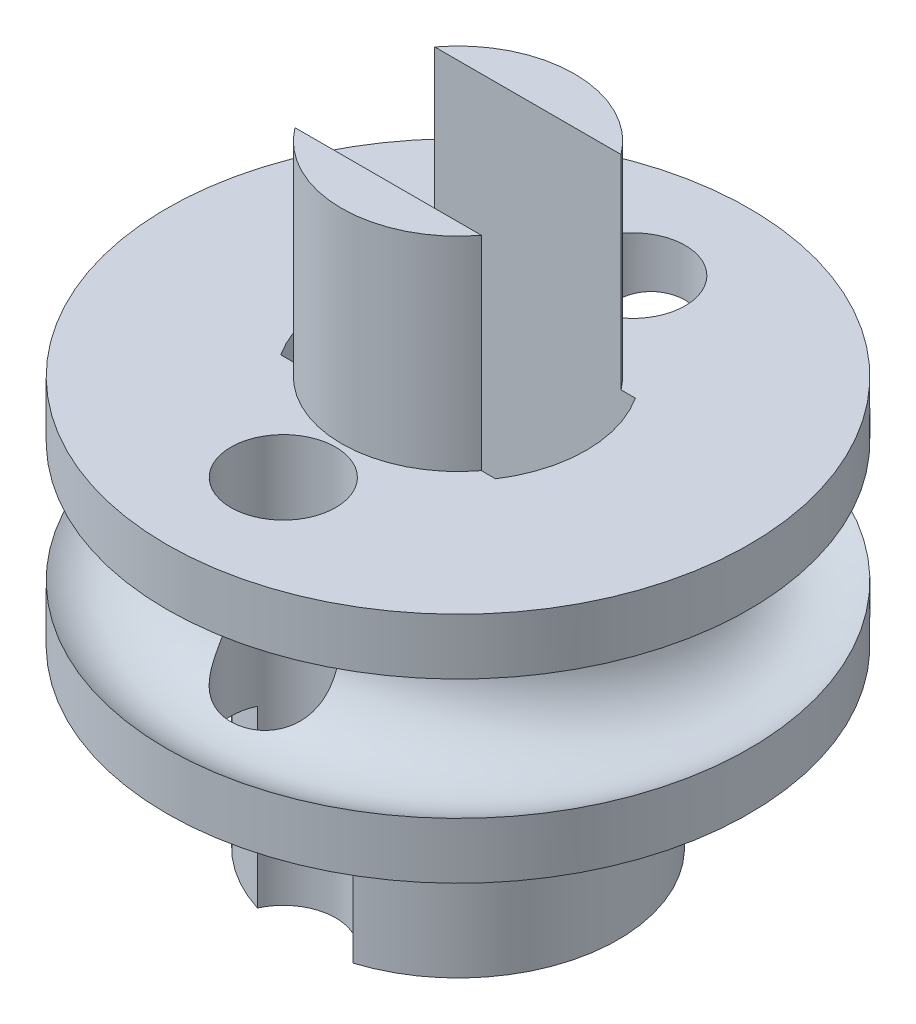
SolidWorks part; units mm, degrees
ref_plane "前视基准面" through (0, 0, 0) normal (0, 0, 1) x (1, 0, 0)
ref_plane "上视基准面" through (0, 0, 0) normal (0, 1, 0) x (1, 0, 0)
ref_plane "右视基准面" through (0, 0, 0) normal (1, 0, 0) x (0, 0, -1)
other "Configuration Table"
sketch "草图1" plane through (0, 0, 0) normal (0, 1, 0) x (1, 0, 0)
  circle A0 centre (0, 0) radius 2.75
  dimension "D1" = 5.5
extrude "凸台-拉伸1" add sketch "草图1" along normal blind 7
sketch "草图2" plane through (0, 7, 0) normal (0, 1, 0) x (1, 0, 0)
  line L0 (-1.8439, 1.2) -> (1.8439, 1.2)
  line L1 (-1.8439, -1.2) -> (1.8439, -1.2)
  circle A0 centre (0, 0) radius 2.2
  dimension "D1" = 4.4
  dimension "D2" = 2.4
extrude "切除-拉伸1" cut sketch "草图2" against normal offset from surface (6 mm away) 1 contours L1 A0 L0 up to face at (0, 0, 2.75)
sketch "草图4" plane through (0, 7, 0) normal (0, 1, 0) x (1, 0, 0)
  line L2 (1.6363, -1.15) -> (-1.6363, -1.15)
  line L3 (1.6363, 1.15) -> (-1.6363, 1.15)
  circle A0 centre (0, 0) radius 2
  circle A1 centre (0, 0) radius 2 construction
  circle A2 centre (0, 0) radius 2
  line M1 (1.8439, -1.2) -> (-1.8439, -1.2)
  line M3 (-1.8439, 1.2) -> (1.8439, 1.2)
  dimension "D1" = 4
  dimension "D2" = 2.3
extrude "凸台-拉伸2" add sketch "草图4" along normal blind 3.5 contours A0 M3 | A0 M1
sketch "草图5" plane through (0, 7, 0) normal (0, 1, 0) x (1, 0, 0)
  circle A0 centre (0, 0) radius 5
  circle A1 centre (0, 0) radius 2.75
  circle A2 centre (0, 0) radius 2.75
  dimension "D2" = 10
  dimension "D1" = 0
extrude "凸台-拉伸3" add sketch "草图5" against normal blind 4
ref_plane "基准面1" through (0, 5, 0) normal (0, -1, 0) x (-1, 0, 0)
sketch "草图6" plane through (0, 5, 0) normal (0, -1, 0) x (-1, 0, 0)
  circle A0 centre (0, 0) radius 4.3
  circle A1 centre (0, 0) radius 5 construction
  dimension "D1" = 0.7
sweep "切除-扫描1" cut path "草图6" circular profile diameter 2.5 parameters "D3"=2.5
sketch "草图13" plane through (0, 3, 0) normal (0, -1, 0) x (1, 0, 0)
  line L0 (0, -3) -> (0, 0) construction
  line L1 (0, 0) -> (0, 3) construction
  line L2 (1.8439, 1.2) -> (-1.8439, 1.2)
  line L3 (-1.8439, -1.2) -> (1.8439, -1.2)
  line L4 (1.8439, 1.2) -> (-1.8439, 1.2) construction
  line L5 (-1.8439, -1.2) -> (1.8439, -1.2) construction
  line L6 (0, 0) -> (-2.2, 0) construction
  circle A0 centre (0, 3) radius 0.9
  circle A1 centre (0, -3) radius 0.9
  arc A2 (1.8439, -1.2) -> (1.8439, 1.2) centre (0, 0) ccw
  arc A3 (-1.8439, 1.2) -> (-1.8439, -1.2) centre (0, 0) ccw
  arc A4 (1.8439, -1.2) -> (1.8439, 1.2) centre (0, 0) ccw construction
  arc A5 (-1.8439, 1.2) -> (-1.8439, -1.2) centre (0, 0) ccw construction
  dimension "D2" = 1.8
  dimension "D3" = 6
  dimension "D1" = 0
extrude "切除-拉伸2" cut sketch "草图13" against normal up to next and the other way up to next
